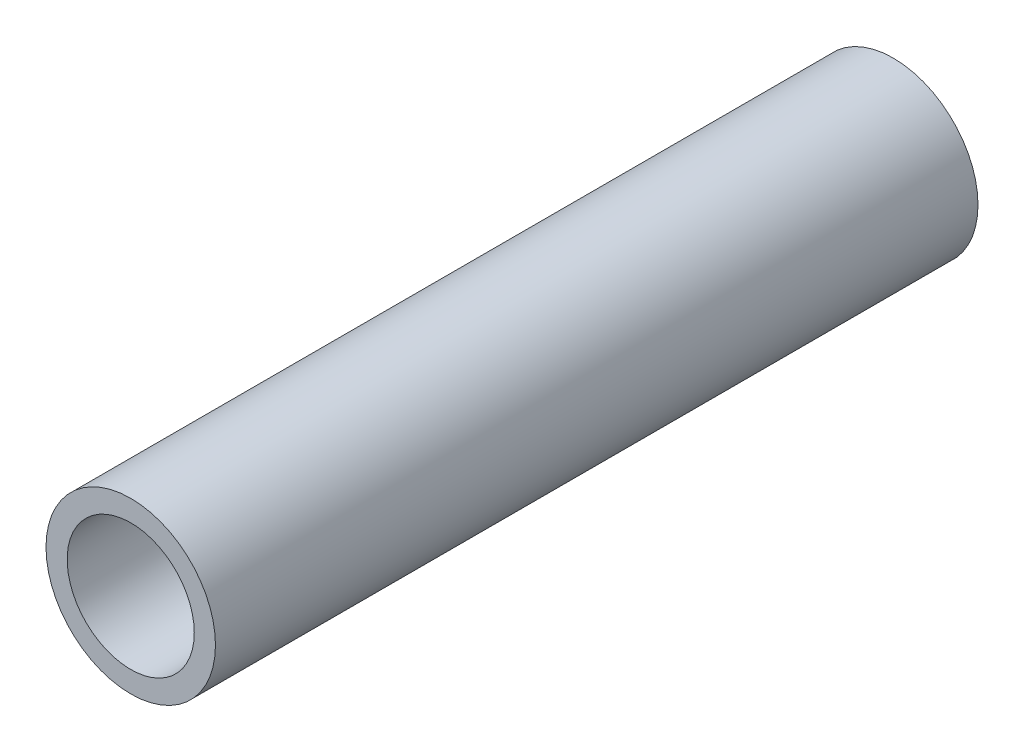
SolidWorks part; units mm, degrees
ref_plane "Front Plane" through (0, 0, 0) normal (0, 0, 1) x (1, 0, 0)
ref_plane "Top Plane" through (0, 0, 0) normal (0, 1, 0) x (1, 0, 0)
ref_plane "Right Plane" through (0, 0, 0) normal (1, 0, 0) x (0, 0, -1)
sketch "Sketch1" plane through (0, 0, 0) normal (0, 0, 1) x (1, 0, 0)
  circle A0 centre (0, 0) radius 20
  dimension "D1" = 40
extrude "Boss-Extrude1" add sketch "Sketch1" along normal blind 180 contours A0
sketch "Sketch2" plane through (0, 0, 180) normal (0, 0, 1) x (1, 0, 0)
  circle A0 centre (0, 0) radius 15
  dimension "D1" = 30
extrude "Cut-Extrude1" cut sketch "Sketch2" against normal blind 180
